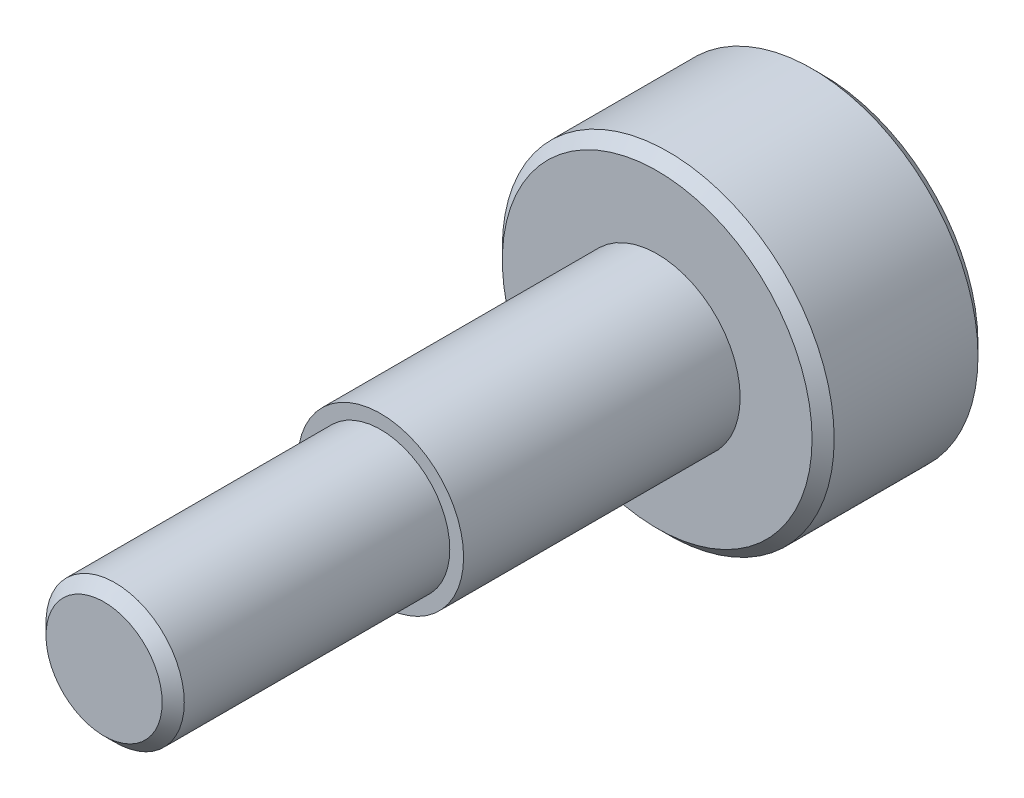
SolidWorks part; units mm, degrees
ref_plane "前视基准面" through (0, 0, 0) normal (0, 0, 1) x (1, 0, 0)
ref_plane "上视基准面" through (0, 0, 0) normal (0, 1, 0) x (1, 0, 0)
ref_plane "右视基准面" through (0, 0, 0) normal (1, 0, 0) x (0, 0, -1)
sketch "草图1" plane through (0, 0, 0) normal (0, 0, 1) x (1, 0, 0)
  circle A0 centre (0, 0) radius 3
  dimension "D1" = 6
extrude "凸台-拉伸1" add sketch "草图1" along normal blind 3
sketch "草图2" plane through (0, 0, 3) normal (0, 0, 1) x (1, 0, 0)
  circle A0 centre (0, 0) radius 1.5
  dimension "D1" = 3
extrude "凸台-拉伸2" add sketch "草图2" along normal blind 5
sketch "草图3" plane through (0, 0, 8) normal (0, 0, 1) x (1, 0, 0)
  circle A0 centre (0, 0) radius 1.25
  dimension "D1" = 2.5
extrude "凸台-拉伸3" add sketch "草图3" along normal blind 5
chamfer "倒角1" distance 0.2 angle 45 3 edges at (1.25, 0, 13) (3, 0, 0) (3, 0, 3)
